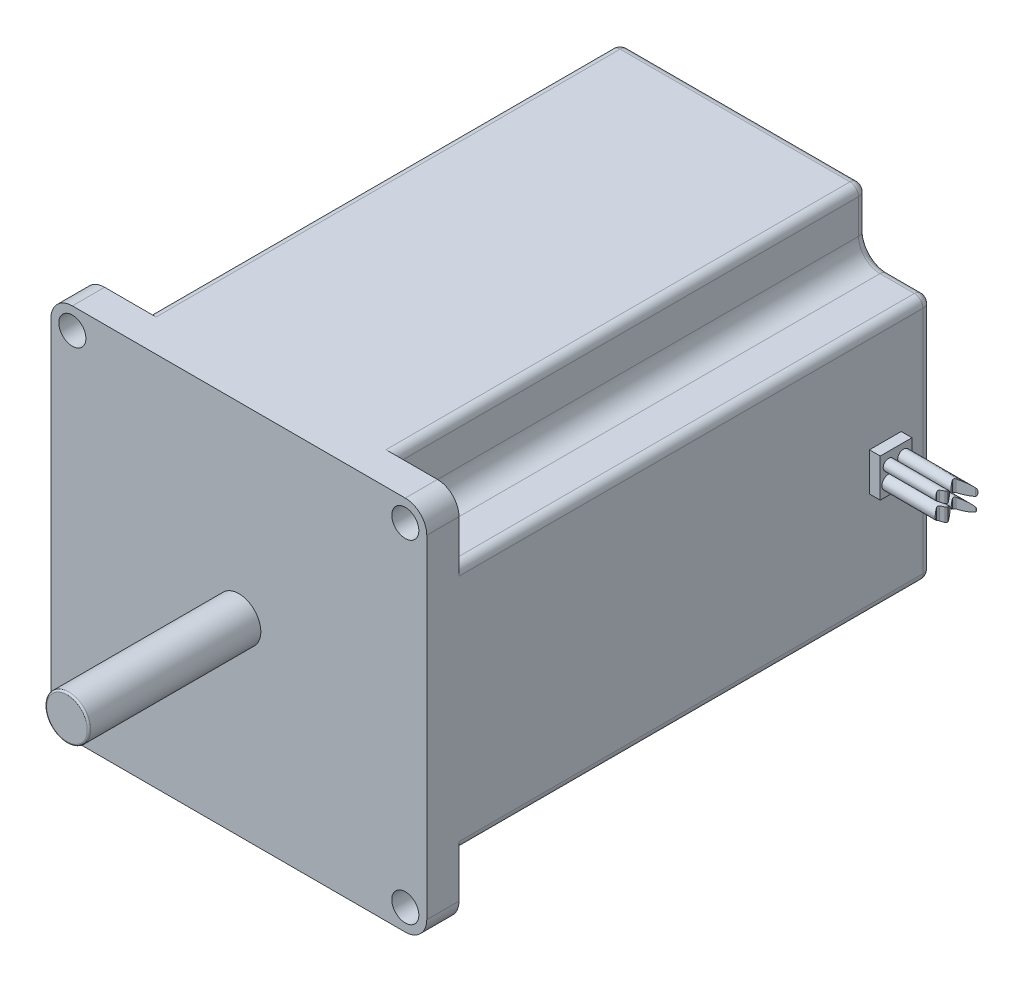
SolidWorks part; units mm, degrees
ref_plane "Front Plane" through (0, 0, 0) normal (0, 0, 1) x (1, 0, 0)
ref_plane "Top Plane" through (0, 0, 0) normal (0, 1, 0) x (1, 0, 0)
ref_plane "Right Plane" through (0, 0, 0) normal (1, 0, 0) x (0, 0, -1)
sketch "Sketch1" plane through (0, 0, 0) normal (0, 0, 1) x (1, 0, 0)
  line L0 (-39.7276, -26.2517) -> (-39.7276, -31.3317)
  line L1 (-47.9826, 13.4358) -> (-42.9026, 13.4358)
  line L2 (-49.2526, 12.1658) -> (-49.2526, -21.8067)
  line L3 (-47.9826, -23.0767) -> (-42.9026, -23.0767)
  line L4 (6.3099, 12.1658) -> (6.3099, -21.8067)
  line L5 (-38.4576, 22.9608) -> (-4.4851, 22.9608)
  line L6 (-39.7276, 21.6908) -> (-39.7276, 16.6108)
  line L7 (-38.4576, -32.6017) -> (-4.4851, -32.6017)
  line L8 (-3.2151, 21.6908) -> (-3.2151, 16.6108)
  line L9 (-0.0401, 13.4358) -> (5.0399, 13.4358)
  line L10 (-3.2151, -26.2517) -> (-3.2151, -31.3317)
  line L11 (-0.0401, -23.0767) -> (5.0399, -23.0767)
  arc A0 (-39.7276, -26.2517) -> (-42.9026, -23.0767) centre (-42.9026, -26.2517) ccw
  arc A1 (-3.2151, -26.2517) -> (-0.0401, -23.0767) centre (-0.0401, -26.2517) cw
  arc A2 (-0.0401, 13.4358) -> (-3.2151, 16.6108) centre (-0.0401, 16.6108) cw
  arc A3 (-39.7276, 16.6108) -> (-42.9026, 13.4358) centre (-42.9026, 16.6108) cw
  arc A4 (-47.9826, 13.4358) -> (-49.2526, 12.1658) centre (-47.9826, 12.1658) ccw
  arc A5 (-49.2526, -21.8067) -> (-47.9826, -23.0767) centre (-47.9826, -21.8067) ccw
  arc A6 (-39.7276, -31.3317) -> (-38.4576, -32.6017) centre (-38.4576, -31.3317) ccw
  arc A7 (-4.4851, -32.6017) -> (-3.2151, -31.3317) centre (-4.4851, -31.3317) ccw
  arc A8 (5.0399, -23.0767) -> (6.3099, -21.8067) centre (5.0399, -21.8067) ccw
  arc A9 (5.0399, 13.4358) -> (6.3099, 12.1658) centre (5.0399, 12.1658) cw
  arc A10 (-4.4851, 22.9608) -> (-3.2151, 21.6908) centre (-4.4851, 21.6908) cw
  arc A11 (-38.4576, 22.9608) -> (-39.7276, 21.6908) centre (-38.4576, 21.6908) ccw
  point P16 (-3.2151, -23.0767)
  point P23 (-49.2526, 13.4358)
  point P26 (-49.2526, -23.0767)
  point P29 (-39.7276, -32.6017)
  point P36 (6.3099, 13.4358)
  point P39 (-3.2151, 22.9608)
  point P42 (-39.7276, 22.9608)
  dimension "D7" = 3.175
  dimension "D8" = 1.27
  dimension "D1" = 36.5125
  dimension "D2" = 36.5125
  dimension "D3" = 55.5625
  dimension "D4" = 55.5625
  dimension "D5" = 9.525
  dimension "D6" = 9.525
extrude "Boss-Extrude1" add sketch "Sketch1" along normal blind 69.85
sketch "Sketch2" plane through (0, 0, 69.85) normal (0, 0, 1) x (1, 0, 0)
  line L0 (-29.4612, 22.9608) -> (-49.2526, 22.9608) construction
  line L1 (-4.4851, 22.9608) -> (-38.4576, 22.9608) construction
  line L2 (-49.2526, 5.1825) -> (-49.2526, 22.9608) construction
  line L3 (-49.2526, 12.1658) -> (-49.2526, -21.8067) construction
  line L5 (-46.0776, 22.9608) -> (3.1349, 22.9608)
  line L6 (-49.2526, 19.7858) -> (-49.2526, -29.4267)
  line L7 (-46.0776, -32.6017) -> (3.1349, -32.6017)
  line L8 (6.3099, 19.7858) -> (6.3099, -29.4267)
  arc A0 (3.1349, 22.9608) -> (6.3099, 19.7858) centre (3.1349, 19.7858) cw
  arc A1 (3.1349, -32.6017) -> (6.3099, -29.4267) centre (3.1349, -29.4267) ccw
  arc A2 (-49.2526, -29.4267) -> (-46.0776, -32.6017) centre (-46.0776, -29.4267) ccw
  arc A3 (-46.0776, 22.9608) -> (-49.2526, 19.7858) centre (-46.0776, 19.7858) ccw
  circle A4 centre (-46.0776, 19.7858) radius 2
  circle A5 centre (3.1349, 19.7858) radius 2
  circle A6 centre (3.1349, -29.4267) radius 2
  circle A7 centre (-46.0776, -29.4267) radius 2
  point P12 (6.3099, 22.9608)
  point P15 (6.3099, -32.6017)
  point P22 (0, 0)
  point P23 (0, 0)
  point P25 (3.1349, 19.731)
  point P28 (3.1349, -29.5172)
  point P30 (0, 0)
  point P31 (-46.0776, -29.527)
  dimension "D3" = 3.175
  dimension "D4" = 4
  dimension "D1" = 55.5625
  dimension "D2" = 55.5625
extrude "Boss-Extrude2" add sketch "Sketch2" along normal blind 4.7625
sketch "Sketch3" plane through (0, 0, 74.6125) normal (0, 0, 1) x (1, 0, 0)
  line L0 (3.1349, 19.7858) -> (-46.0776, -29.4267) construction
  line L1 (-46.0776, 19.7858) -> (3.1349, -29.4267) construction
  circle A0 centre (-21.4714, -4.8205) radius 3.25
  dimension "D1" = 6.5
extrude "Boss-Extrude3" add sketch "Sketch3" along normal blind 25.4
fillet "Fillet1" radius 1.27 24 edges at (-39.7276, -28.7917, 0) (-39.3557, -32.2297, 0) (-21.4714, -32.6017, 0) (-3.5871, -32.2297, 0) (-3.2151, -28.7917, 0) (-2.2852, -24.0067, 0) (2.4999, -23.0767, 0) (5.9379, -22.7047, 0) (6.3099, -4.8205, 0) (5.9379, 13.0638, 0) (2.4999, 13.4358, 0) (-2.2852, 14.3657, 0) (-3.2151, 19.1508, 0) (-3.5871, 22.5888, 0) (-21.4714, 22.9608, 0) (-39.3557, 22.5888, 0) (-39.7276, 19.1508, 0) (-40.6576, 14.3657, 0) (-45.4426, 13.4358, 0) (-48.8807, 13.0638, 0) (-49.2526, -4.8205, 0) (-48.8807, -22.7047, 0) (-45.4426, -23.0767, 0) (-40.6576, -24.0067, 0)
fillet "Fillet2" radius 0.254 1 edges at (-18.2214, -4.8205, 100.0125)
sketch "Sketch4" plane through (6.3099, 0, 0) normal (1, 0, 0) x (0, 0, -1)
  line L0 (-1.27, -4.8205) -> (-51.8698, -4.8205) construction
  line L1 (-1.27, -21.8067) -> (-1.27, 12.1658) construction
  line L3 (-7.9375, -2.4392) -> (-5.715, -2.4392)
  line L4 (-9.2075, -3.7092) -> (-9.2075, -5.9317)
  line L5 (-7.9375, -7.2017) -> (-5.715, -7.2017)
  line L6 (-4.445, -3.7092) -> (-4.445, -5.9317)
  line L7 (-9.2075, -2.4392) -> (-4.445, -7.2017) construction
  line L8 (-9.2075, -7.2017) -> (-4.445, -2.4392) construction
  arc A0 (-7.9375, -2.4392) -> (-9.2075, -3.7092) centre (-7.9375, -3.7092) ccw
  arc A1 (-9.2075, -5.9317) -> (-7.9375, -7.2017) centre (-7.9375, -5.9317) ccw
  arc A2 (-5.715, -7.2017) -> (-4.445, -5.9317) centre (-5.715, -5.9317) ccw
  arc A3 (-5.715, -2.4392) -> (-4.445, -3.7092) centre (-5.715, -3.7092) cw
  circle A4 centre (-7.9375, -3.7092) radius 0.8
  circle A5 centre (-5.715, -3.7092) radius 0.8774
  circle A6 centre (-7.9375, -5.9317) radius 0.9978
  circle A7 centre (-5.715, -5.9317) radius 0.748
  point P4 (-6.8262, -4.8205)
  dimension "D4" = 1.27
  dimension "D1" = 4.7625
  dimension "D2" = 4.7625
  dimension "D3" = 3.175
extrude "Boss-Extrude4" add sketch "Sketch4" along normal blind 12.7 contours A6 | A7 | A5 | A4
sketch "Sketch5" plane through (0, 0, 0) normal (0, 1, 0) x (1, 0, 0)
  line L0 (19.4016, -15.4833) -> (15.569, -8.5497)
  line L1 (15.697, -8.1909) -> (16.2625, -7.9647)
  line L2 (16.384, -7.5948) -> (15.426, -6.0531)
  line L3 (15.5731, -5.6745) -> (17.8303, -5.0407)
  line L4 (17.9579, -4.6349) -> (14.4779, -0.3984)
  line L5 (19.4016, -15.4833) -> (25.6325, -10.7752)
  line L6 (25.6325, -10.7752) -> (15.905, 0.4535)
  line L7 (15.905, 0.4535) -> (14.4779, -0.3984)
  arc A0 (15.569, -8.5497) -> (15.697, -8.1909) centre (15.7913, -8.4268) cw
  arc A1 (16.2625, -7.9647) -> (16.384, -7.5948) centre (16.1682, -7.7289) ccw
  arc A2 (15.426, -6.0531) -> (15.5731, -5.6745) centre (15.6417, -5.9191) cw
  arc A3 (17.8303, -5.0407) -> (17.9579, -4.6349) centre (17.7616, -4.7961) ccw
  dimension "D1" = 0.254
extrude "Cut-Extrude1" cut sketch "Sketch5" against normal blind 12.7
sketch "Sketch6" plane through (6.3099, 0, 0) normal (1, 0, 0) x (0, 0, -1)
  line L0 (-1.27, -4.8205) -> (-21.836, -4.8205) construction
  line L1 (-1.27, -21.8067) -> (-1.27, 12.1658) construction
  line L3 (-9.1718, -1.994) -> (-4.4887, -1.994)
  line L4 (-9.1718, -1.994) -> (-9.1718, -7.647)
  line L5 (-9.1718, -7.647) -> (-4.4887, -7.647)
  line L6 (-4.4887, -1.994) -> (-4.4887, -7.647)
  line L7 (-9.1718, -1.994) -> (-4.4887, -7.647) construction
  line L8 (-9.1718, -7.647) -> (-4.4887, -1.994) construction
  point P4 (-6.8303, -4.8205)
extrude "Boss-Extrude5" add sketch "Sketch6" along normal blind 1.5875
